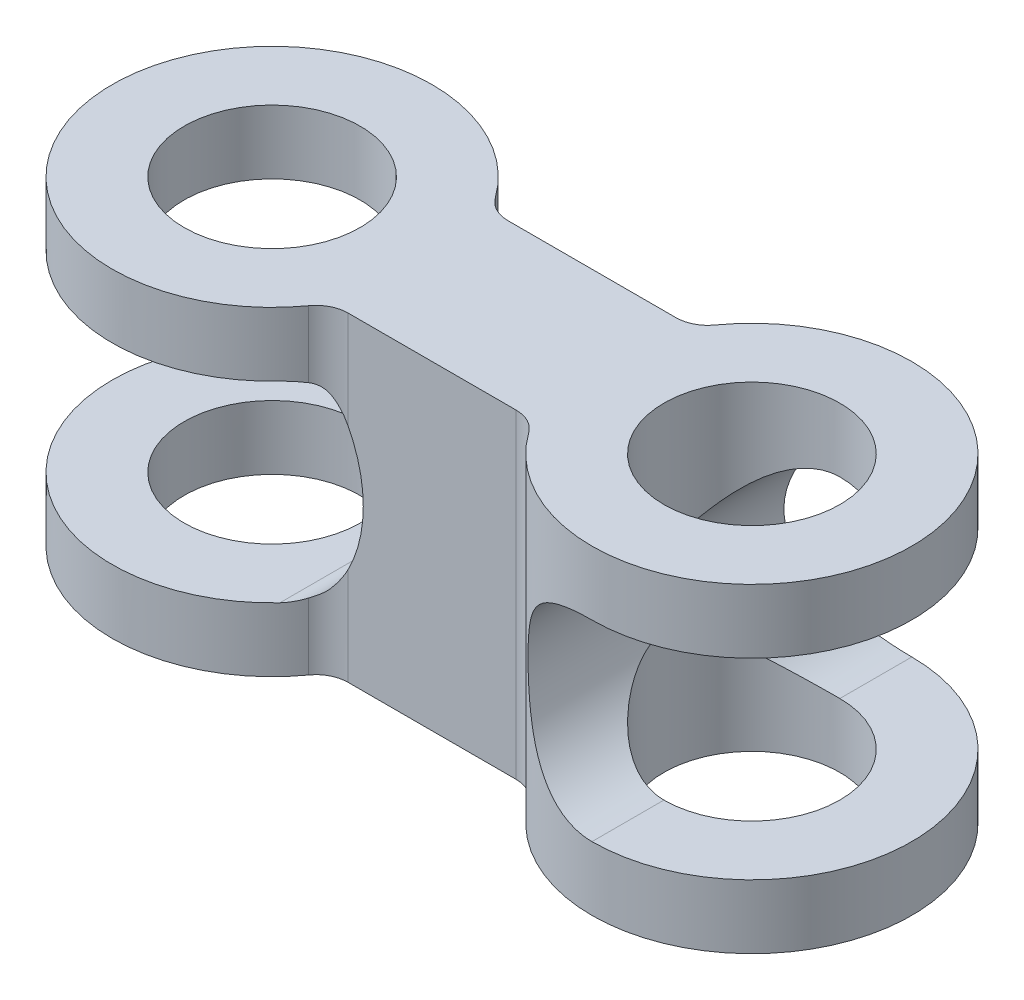
SolidWorks part; units mm, degrees
ref_plane "Front Plane" through (0, 0, 0) normal (0, 0, 1) x (1, 0, 0)
ref_plane "Top Plane" through (0, 0, 0) normal (0, 1, 0) x (1, 0, 0)
ref_plane "Right Plane" through (0, 0, 0) normal (1, 0, 0) x (0, 0, -1)
sketch "Sketch1" plane through (0, 0, 0) normal (0, 1, 0) x (1, 0, 0)
  line L1 (0, 2.5) -> (7.5, 2.5)
  line L2 (0, 2.5) -> (0, -2.5)
  line L3 (0, -2.5) -> (7.5, -2.5)
  line L4 (7.5, 2.5) -> (7.5, -2.5)
  dimension "D1" = 5
  dimension "D2" = 7.5
extrude "Boss-Extrude1" add sketch "Sketch1" along normal blind 10
sketch "Sketch2" plane through (0, 0, 0) normal (0, 1, 0) x (1, 0, 0)
  circle A0 centre (0, 0) radius 5
  dimension "D1" = 10
sketch "Sketch3" plane through (0, 0, 0) normal (0, 1, 0) x (1, 0, 0)
  circle A0 centre (0, 0) radius 2.75
  dimension "D1" = 5.5
extrude "Boss-Extrude2" add sketch "Sketch2" along normal up to surface (10 mm away) up to face at (3.75, 10, 0)
extrude "Cut-Extrude1" cut sketch "Sketch3" along normal up to next
sketch "Sketch4" plane through (0, 0, 0) normal (0, 0, 1) x (1, 0, 0)
  line L0 (0, 0) -> (0, 10) construction
  line L1 (2.75, 10) -> (-2.75, 10) construction
  line L2 (0, 8) -> (-5, 8)
  line L3 (-5, 10) -> (-5, 0) construction
  line L4 (0, 2) -> (-5, 2)
  line L5 (-5, 8) -> (-5, 2)
  line L6 (0, 5) -> (4.1, 5) construction
  line L7 (0, 8) -> (4.1, 8)
  line L8 (4.1, 8) -> (4.1, 2) construction
  line L9 (4.1, 2) -> (0, 2)
  arc A1 (4.1, 8) -> (4.1, 2) centre (1.125, 5) cw
  point P15 (5.35, 5)
  dimension "D1" = 2
  dimension "D2" = 6
  dimension "D3" = 4.1
  dimension "D4" = 1.25
extrude "Cut-Extrude2" cut sketch "Sketch4" against normal through all both and the other way through all
fillet "Fillet1" radius 1 2 edges at (4.3301, 8.8764, -2.5) (4.3301, 1.1236, 2.5)
fillet "Fillet3" radius 1 2 edges at (4.1, 2, 0.0021) (4.1, 8, -0.0021)
fillet "Fillet4" radius 1 2 edges at (4.3301, 1.1312, -2.5) (4.3301, 8.8688, 2.5)
mirror "Mirror1" about plane through (7.5, 10, -2.5) normal (-1, 0, 0) of "Fillet1", "Boss-Extrude2", "Cut-Extrude1", "Boss-Extrude1"
sketch "Sketch6" plane through (0, 0, 0) normal (0, 0, 1) x (1, 0, 0)
  line L0 (17.75, 10) -> (12.25, 10) construction
  line L1 (17.75, 10) -> (12.25, 10) construction
  line L2 (15, 10) -> (15, 0) construction
  line L3 (10.9388, 0) -> (20, 0) construction
  line L4 (15, 8) -> (20, 8)
  line L5 (20, 0) -> (20, 10) construction
  line L6 (20, 8) -> (20, 2)
  line L7 (20, 2) -> (15, 2)
  arc A0 (15, 8) -> (15, 2) centre (15, 5) ccw
  dimension "D1" = 6
extrude "Cut-Extrude3" cut sketch "Sketch6" against normal through all both and the other way through all
